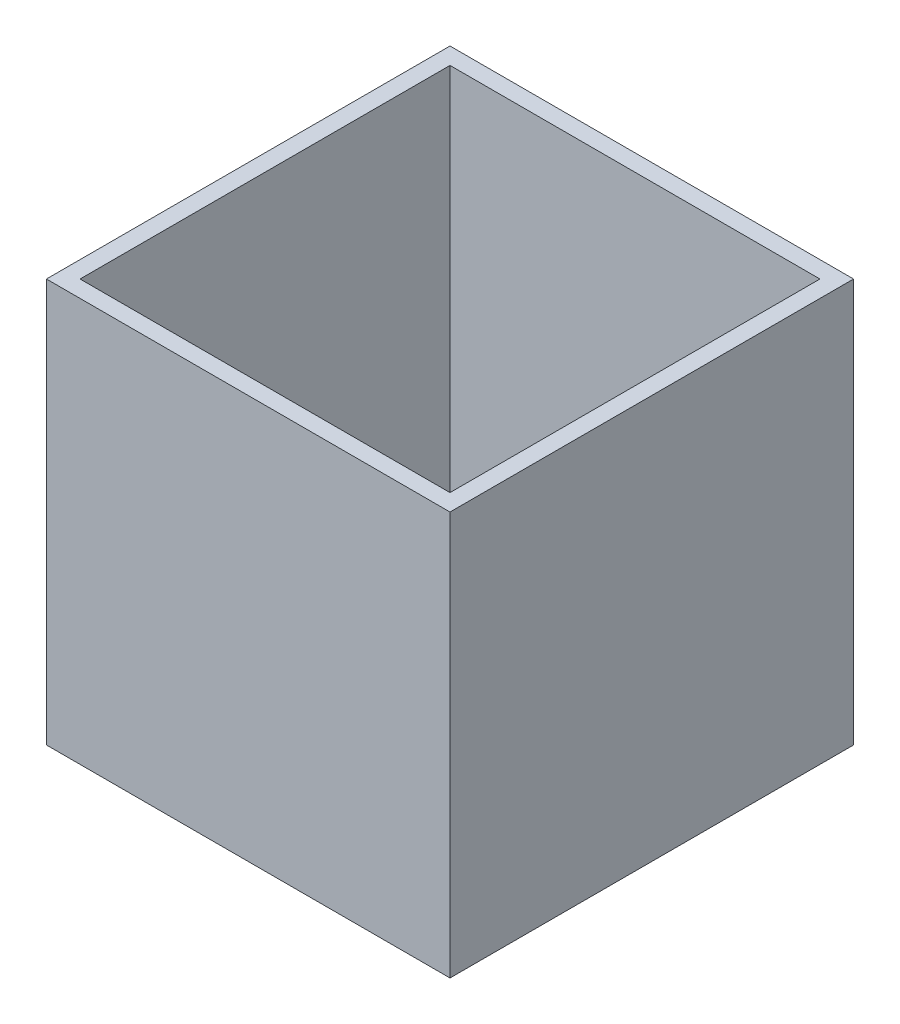
SolidWorks part; units mm, degrees
ref_plane "Front Plane" through (0, 0, 0) normal (0, 0, 1) x (1, 0, 0)
ref_plane "Top Plane" through (0, 0, 0) normal (0, 1, 0) x (1, 0, 0)
ref_plane "Right Plane" through (0, 0, 0) normal (1, 0, 0) x (0, 0, -1)
sketch "Sketch1" plane through (0, 0, 0) normal (0, 0, 1) x (1, 0, 0)
  line L1 (-11.0772, 255.1547) -> (293.7228, 255.1547)
  line L2 (-11.0772, 255.1547) -> (-11.0772, -49.6453)
  line L3 (-11.0772, -49.6453) -> (293.7228, -49.6453)
  line L4 (293.7228, 255.1547) -> (293.7228, -49.6453)
  line L5 (141.3228, -49.6453) -> (141.3228, 255.1547) construction
  line L6 (-11.0772, 102.7547) -> (293.7228, 102.7547) construction
  point P4 (14.0462, -43.2184)
  point P196 (141.3228, 102.7547)
  dimension "D1" = 304.8
  dimension "D2" = 304.8
extrude "Boss-Extrude2" add sketch "Sketch1" along normal blind 304.8
shell "Shell1" thickness 12.7
sketch "Sketch2" plane through (0, -36.9453, 0) normal (0, 1, 0) x (1, 0, 0)
  line L0 (141.3228, -12.7) -> (141.3228, -292.1) construction
  line L1 (112.3228, -127.9) -> (170.3228, -127.9)
  line L2 (112.3228, -127.9) -> (112.3228, -176.9)
  line L3 (112.3228, -176.9) -> (170.3228, -176.9)
  line L4 (170.3228, -127.9) -> (170.3228, -176.9)
  line L5 (141.3228, -176.9) -> (141.3228, -127.9) construction
  line L6 (112.3228, -152.4) -> (170.3228, -152.4) construction
  line L7 (281.0228, -12.7) -> (1.6228, -12.7) construction
  line L8 (281.0228, -292.1) -> (1.6228, -292.1) construction
  line L9 (1.6228, -152.4) -> (281.0228, -152.4) construction
  line L10 (1.6228, -292.1) -> (1.6228, -12.7) construction
  line L11 (281.0228, -292.1) -> (281.0228, -12.7) construction
  line L12 (115.8228, -127.9) -> (115.8228, -131.4) construction
  line L19 (115.8228, -131.4) -> (112.3228, -131.4) construction
  line L20 (166.8228, -131.4) -> (166.8228, -127.9) construction
  line L21 (166.8228, -127.9) -> (166.8228, -131.4) construction
  line L22 (166.8228, -131.4) -> (170.3228, -131.4) construction
  line L23 (166.8228, -176.9) -> (166.8228, -173.4) construction
  line L24 (166.8228, -173.4) -> (170.3228, -173.4) construction
  line L25 (115.8228, -173.4) -> (115.8228, -176.9) construction
  line L26 (115.8228, -176.9) -> (115.8228, -173.4) construction
  line L27 (115.8228, -173.4) -> (112.3228, -173.4) construction
  circle A1 centre (115.8228, -131.4) radius 3.8778
  circle A2 centre (166.8228, -131.4) radius 3.8778
  circle A3 centre (166.8228, -173.4) radius 3.8778
  circle A4 centre (115.8228, -173.4) radius 3.8778
  point P17 (141.3228, -152.4)
  point P140 (141.3228, -152.4)
  dimension "D5" = 3.5
  dimension "D1" = 58
  dimension "D2" = 49
  dimension "D3" = 3.5
  dimension "D4" = 3.5
  dimension "D6" = 3.5
  dimension "D7" = 3.5
  dimension "D8" = 3.5
  dimension "D9" = 3.5
  dimension "D10" = 3.5
extrude "Boss-Extrude3" add sketch "Sketch2" along normal blind 6 contours L3 A4 L2 | L3 A3 L4 | L4 A2 L1 | A1
hole_wizard "M2.5x0.45 Tapped Hole3" positions "Sketch8" profile "Sketch9" tap size "M2.5x0.45" standard "ANSI Metric" end condition up to next
sketch "Sketch8" plane through (0, -30.9453, 0) normal (0, 1, 0) x (1, 0, 0)
  point P0 (115.8228, -131.4)
  point P3 (166.8228, -131.4)
  point P6 (166.8228, -173.4)
  point P9 (115.8228, -173.4)
sketch "Sketch9" plane through (115.8228, -30.9453, 131.4) normal (1, 0, 0) x (0, 0, 1)
  line L0 (0, 0) -> (0, 18.7)
  line L1 (0, 18.7) -> (1.025, 18.7)
  line L2 (1.025, 18.7) -> (1.025, 0)
  line L5 (1.025, 0) -> (0, 0)
  line L11 (0, -6.35) -> (0, 107.95) construction
  dimension "Thru Tap Drill Dia." = 2.05
  dimension "Thru Tap Drill Depth" = 18.7
cosmetic thread "Hole Thread12" parameters "D2"=2.5
cosmetic thread "Hole Thread13" parameters "D2"=2.5
cosmetic thread "Hole Thread14" parameters "D2"=2.5
cosmetic thread "Hole Thread15" parameters "D2"=2.5
